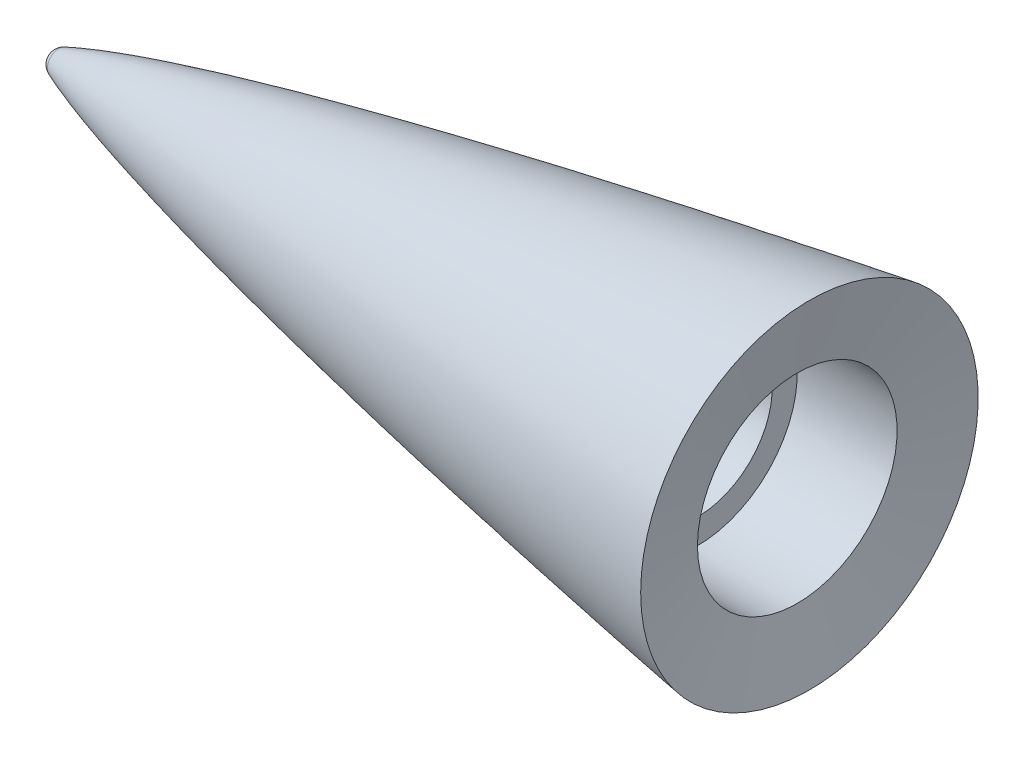
SolidWorks part; units mm, degrees
material "6061-T6 (SS)"
ref_plane "Front Plane" through (0, 0, 0) normal (0, 0, 1) x (1, 0, 0)
ref_plane "Top Plane" through (0, 0, 0) normal (0, 1, 0) x (1, 0, 0)
ref_plane "Right Plane" through (0, 0, 0) normal (1, 0, 0) x (0, 0, -1)
sketch "Sketch1" plane through (0, 0, 0) normal (0, 1, 0) x (1, 0, 0)
  line L0 (0, 0) -> (113.3431, 0) construction
  line L1 (1.6973, 0) -> (39.4694, 0)
  line L2 (83.9194, 12.7) -> (96.6194, 12.7)
  line L3 (96.6194, 12.7) -> (98.1654, 21.4679)
  line L4 (83.9194, 9.525) -> (58.5194, 9.525)
  line L5 (83.9194, 12.7) -> (82.8669, 18.9622) construction
  line L6 (39.4694, 0) -> (39.4694, 6.35)
  line L7 (58.5194, 9.525) -> (58.5194, 6.35)
  line L8 (83.9194, 12.7) -> (83.9194, 9.525)
  line L9 (58.5194, 6.35) -> (39.4694, 6.35)
  arc A0 (2.6821, 1.4686) -> (1.6973, 0) centre (3.2848, 0) ccw
  spline S0 degree 4 poles (0, 0) (0.0034, 0.0099) (0.0124, 0.0287) (0.036, 0.0594) (0.0734, 0.1004) (0.1241, 0.1478) (0.1961, 0.208) (0.3018, 0.2875) (0.4718, 0.4021) (0.7529, 0.5714) (1.2295, 0.826) (2.0659, 1.2203) (3.5324, 1.8251) (5.9654, 2.7008) (9.9595, 3.9615) (15.3529, 5.459) (21.8477, 7.0868) (29.0559, 8.7493) (36.2876, 10.3139) (43.5327, 11.8013) (50.7947, 13.2272) (58.0593, 14.5995) (64.4352, 15.7629) (69.8852, 16.7323) (74.4605, 17.5301) (78.0669, 18.1509) (81.7865, 18.7815) (85.3087, 19.3727) (89.1704, 20.0106) (92.4601, 20.5499) (97.1008, 21.2989) (100.2743, 21.8052) (104.805, 22.5216) (106.4979, 22.7829) (108.0668, 23.0282) knots 0 0 0 0 0 0.000378 0.000756 0.001385 0.00201 0.00288 0.004147 0.006163 0.009417 0.014733 0.02367 0.039565 0.066726 0.108156 0.174994 0.241832 0.30867 0.375509 0.442347 0.509185 0.576023 0.642862 0.676281 0.7097 0.743119 0.776538 0.809957 0.843376 0.876795 0.910214 0.955107 1 1 1 1 1 construction
  spline S1 degree 4 poles (2.6821, 1.4686) (2.9821, 1.5917) (3.9828, 1.987) (6.0755, 2.7356) (9.9593, 3.9614) (15.3526, 5.4589) (21.8473, 7.0867) (29.0554, 8.7492) (36.2869, 10.3137) (43.5319, 11.8011) (50.7938, 13.227) (58.0582, 14.5993) (64.434, 15.7626) (69.8839, 16.7321) (74.4591, 17.5298) (78.0654, 18.1507) (81.785, 18.7813) (85.3071, 19.3724) (89.1687, 20.0104) (92.4584, 20.5496) (95.6643, 21.067) (97.3334, 21.3349) (98.165, 21.4679) (98.1654, 21.4679) knots 0.027847 0.027847 0.027847 0.027847 0.027847 0.039565 0.066726 0.108156 0.174994 0.241832 0.30867 0.375509 0.442347 0.509185 0.576023 0.642862 0.676281 0.7097 0.743119 0.776538 0.809957 0.843376 0.876795 0.910214 0.910233 0.910233 0.910233 0.910233 0.910233
  dimension "D5" = 6.35
  dimension "D8" = 100
  dimension "D3" = 12.7
  dimension "D10" = 1.5875
  dimension "D2" = 12.7
  dimension "D4" = 25.4
  dimension "D6" = 9.525
  dimension "D7" = 6.35
  dimension "D9" = 19.05
revolve "Revolve2" add sketch "Sketch1" angle 360 about L0
